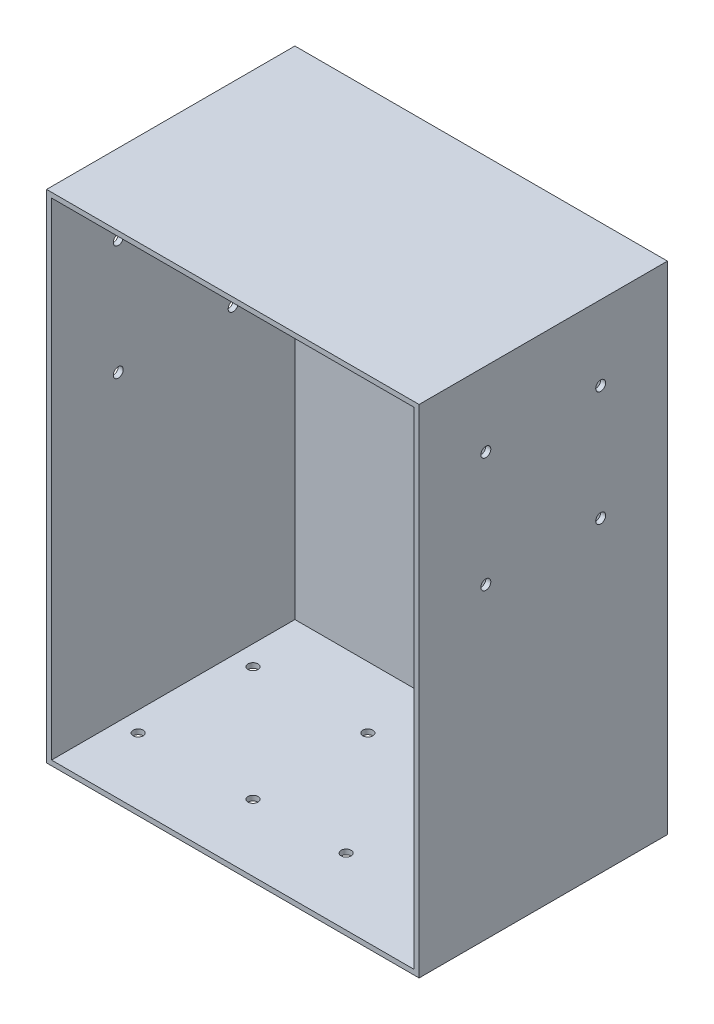
SolidWorks part; units mm, degrees
ref_plane "Ön Düzlem" through (0, 0, 0) normal (0, 0, 1) x (1, 0, 0)
ref_plane "Üst Düzlem" through (0, 0, 0) normal (0, 1, 0) x (1, 0, 0)
ref_plane "Sağ Düzlem" through (0, 0, 0) normal (1, 0, 0) x (0, 0, -1)
sketch "Çizim1" plane through (0, 0, 0) normal (0, 0, 1) x (1, 0, 0)
  line L1 (0, 0) -> (-300, 0)
  line L2 (0, 0) -> (0, 400)
  line L3 (0, 400) -> (-300, 400)
  line L4 (-300, 0) -> (-300, 400)
  dimension "D1" = 300
  dimension "D2" = 400
extrude "Yükseklik-Ekstrüzyon1" add sketch "Çizim1" along normal blind 200
sketch "Çizim2" plane through (0, 0, 0) normal (1, 0, 0) x (0, 0, -1)
  line L0 (0, 0) -> (0, 400) construction
  line L1 (-200, 400) -> (0, 400) construction
  circle A0 centre (-146.25, 340) radius 4
  circle A1 centre (-53.75, 340) radius 4
  circle A2 centre (-146.25, 247.5) radius 4
  circle A3 centre (-53.75, 247.5) radius 4
  dimension "D1" = 92.5
  dimension "D2" = 8
  dimension "D3" = 8
  dimension "D4" = 53.75
  dimension "D5" = 60
  dimension "D6" = 8
  dimension "D7" = 8
  dimension "D8" = 92.5
  dimension "D9" = 92.5
shell "İç Boşaltma1" thickness 4
extrude "Kes-Ekstrüzyon1" cut sketch "Çizim2" against normal up to next
ref_plane "Düzlem1" through (-150, 0, 0) normal (1, 0, 0) x (0, 0, -1)
mirror "Aynalama1" about plane through (-150, 0, 0) normal (1, 0, 0) of "Kes-Ekstrüzyon1"
sketch "Çizim4" plane through (0, 0, 0) normal (0, -1, 0) x (1, 0, 0)
  line L0 (-300, 200) -> (0, 200) construction
  line L1 (-300, 200) -> (-300, 0) construction
  line L2 (-150, 0) -> (-150, 68.9744) construction
  line L3 (-300, 0) -> (0, 0) construction
  circle A0 centre (-280, 146.25) radius 4
  circle A1 centre (-280, 53.75) radius 4
  circle A2 centre (-187.5, 146.25) radius 4
  circle A3 centre (-187.5, 53.75) radius 4
  circle A4 centre (-20, 146.25) radius 4
  circle A5 centre (-20, 53.75) radius 4
  circle A6 centre (-112.5, 53.75) radius 4
  circle A7 centre (-112.5, 146.25) radius 4
  dimension "D1" = 8
  dimension "D2" = 8
  dimension "D3" = 92.5
  dimension "D4" = 53.75
  dimension "D5" = 8
  dimension "D6" = 92.5
  dimension "D7" = 8
  dimension "D8" = 92.5
  dimension "D9" = 92.5
  dimension "D10" = 20
extrude "Kes-Ekstrüzyon2" cut sketch "Çizim4" against normal up to next
